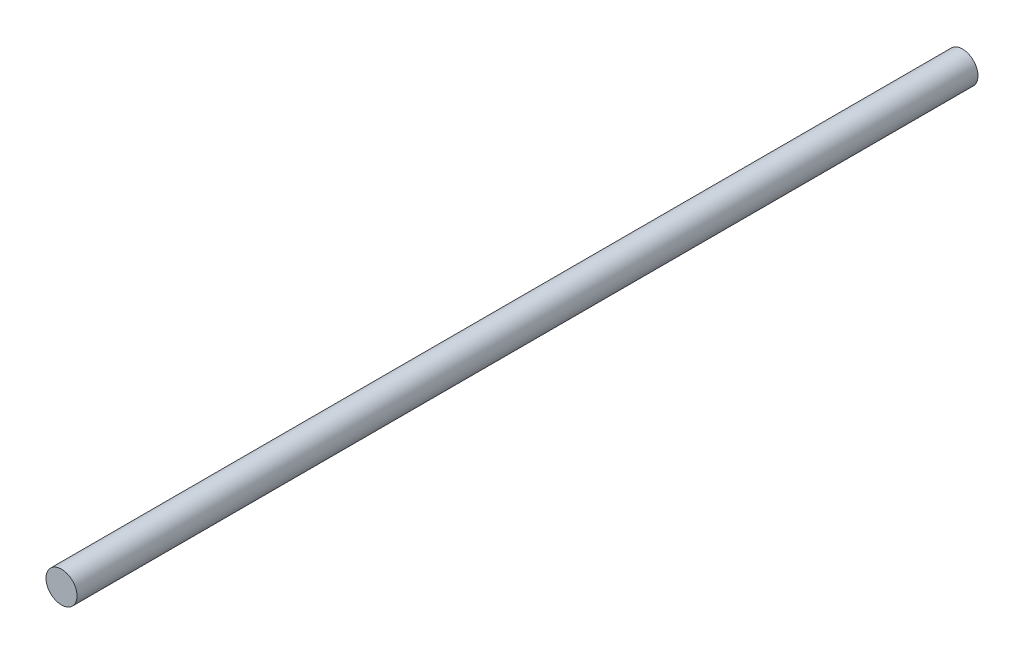
SolidWorks part; units mm, degrees
ref_plane "Front Plane" through (0, 0, 0) normal (0, 0, 1) x (1, 0, 0)
ref_plane "Top Plane" through (0, 0, 0) normal (0, 1, 0) x (1, 0, 0)
ref_plane "Right Plane" through (0, 0, 0) normal (1, 0, 0) x (0, 0, -1)
sketch "Sketch1" plane through (0, 0, 0) normal (0, 0, 1) x (1, 0, 0)
  circle A0 centre (0, 0) radius 5
extrude "Boss-Extrude1" add sketch "Sketch1" along normal blind 290 contours A0
